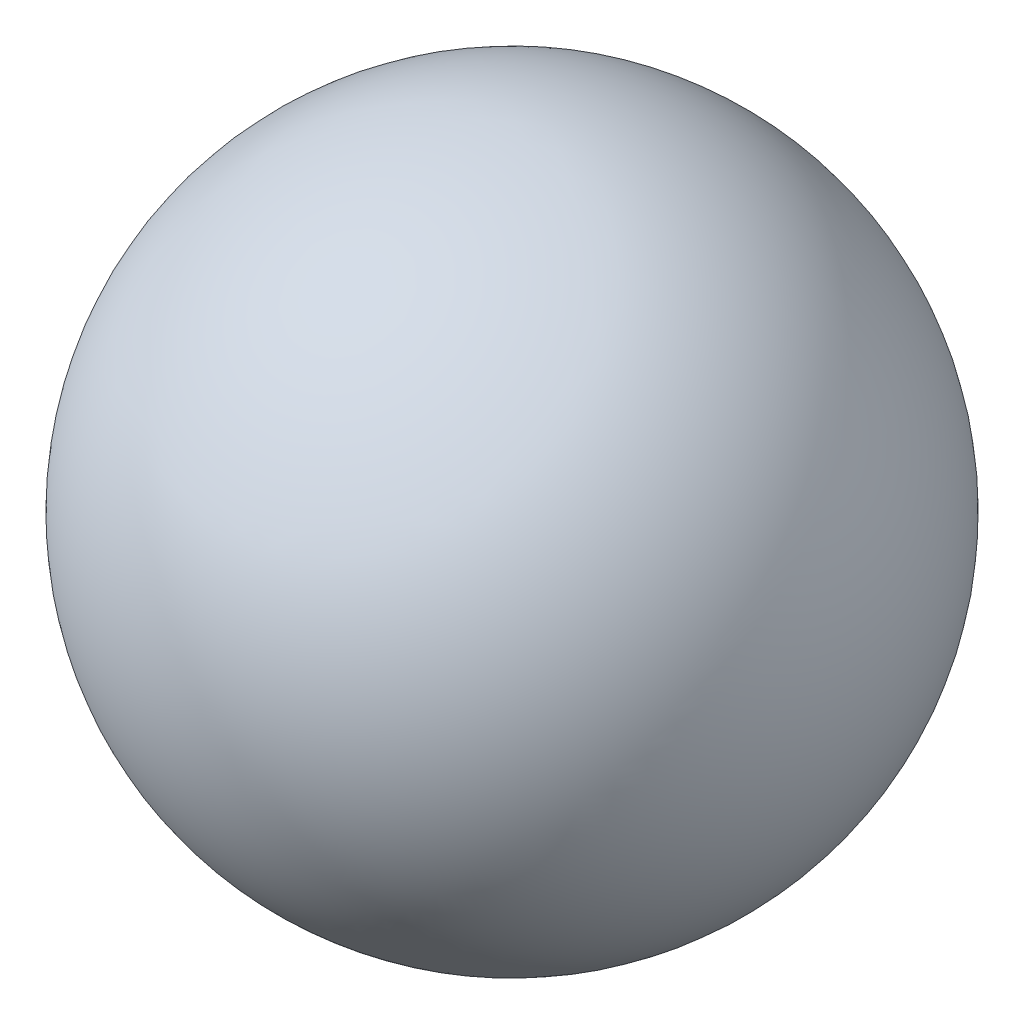
SolidWorks part; units mm, degrees
material "Pure Gold"
ref_plane "Front Plane" through (0, 0, 0) normal (0, 0, 1) x (1, 0, 0)
ref_plane "Top Plane" through (0, 0, 0) normal (0, 1, 0) x (1, 0, 0)
ref_plane "Right Plane" through (0, 0, 0) normal (1, 0, 0) x (0, 0, -1)
sketch "Sketch1" plane through (0, 0, 0) normal (0, 1, 0) x (1, 0, 0)
  arc A0 (-6.841, 10.7) -> (6.841, -10.7) centre (0, 0) cw
ref_axis "Axis1" through (0, 0, 0) along (-0.5387, 0, -0.8425)
revolve "Revolve-Thin1" add sketch "Sketch1" angle 360 about axis through (0, 0, 0) along (-0.5387, 0, -0.8425)
